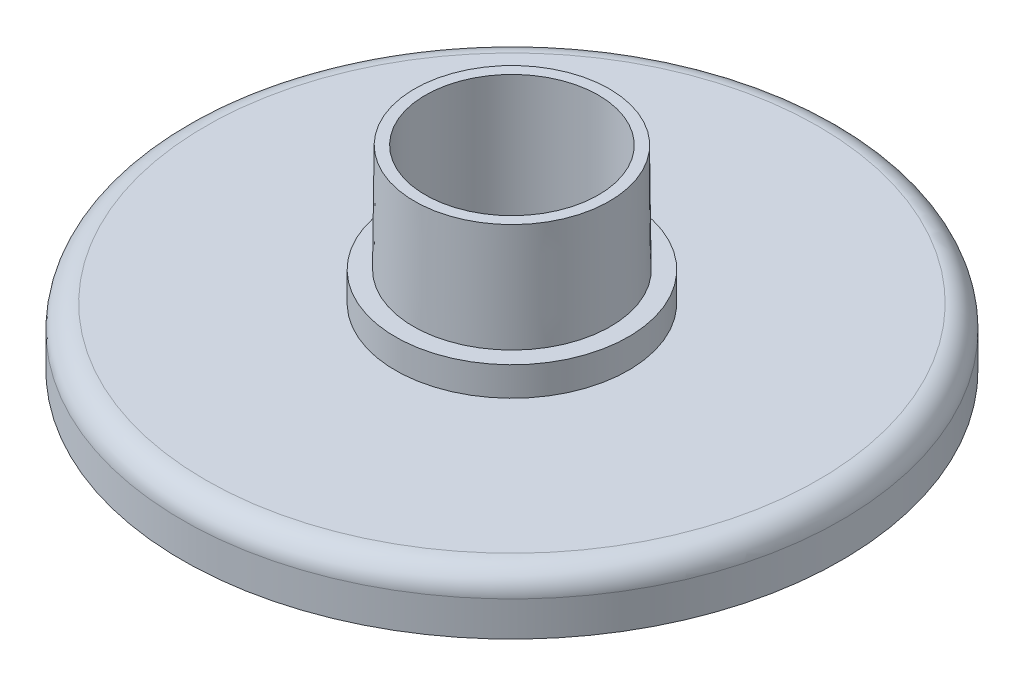
SolidWorks part; units mm, degrees
ref_plane "Front Plane" through (0, 0, 0) normal (0, 0, 1) x (1, 0, 0)
ref_plane "Top Plane" through (0, 0, 0) normal (0, 1, 0) x (1, 0, 0)
ref_plane "Right Plane" through (0, 0, 0) normal (1, 0, 0) x (0, 0, -1)
sketch "Sketch1" plane through (0, 0, 0) normal (1, 0, 0) x (0, 0, -1)
  line L0 (-7.46, 0) -> (-28.415, 0)
  line L1 (-28.415, 0) -> (-28.415, 3)
  line L2 (-26.415, 5) -> (-10.05, 5)
  line L3 (-10.05, 5) -> (-10.05, 7.5)
  line L4 (-10.05, 7.5) -> (-8.5, 7.5)
  line L5 (-8.5, 7.5) -> (-8.4, 16.8)
  line L6 (-8.4, 16.8) -> (-7.46, 16.8)
  line L7 (-7.46, 16.8) -> (-7.46, 0)
  line L8 (0, 0) -> (0, 23.387) construction
  arc A0 (-28.415, 3) -> (-26.415, 5) centre (-26.415, 3) cw
  dimension "D3" = 2
  dimension "D1" = 56.83
  dimension "D2" = 5
  dimension "D4" = 14.92
  dimension "D5" = 17
  dimension "D6" = 16.8
  dimension "D7" = 16.8
  dimension "D8" = 20.1
  dimension "D9" = 2.5
revolve "Revolve1" add sketch "Sketch1" angle 360 about L8
